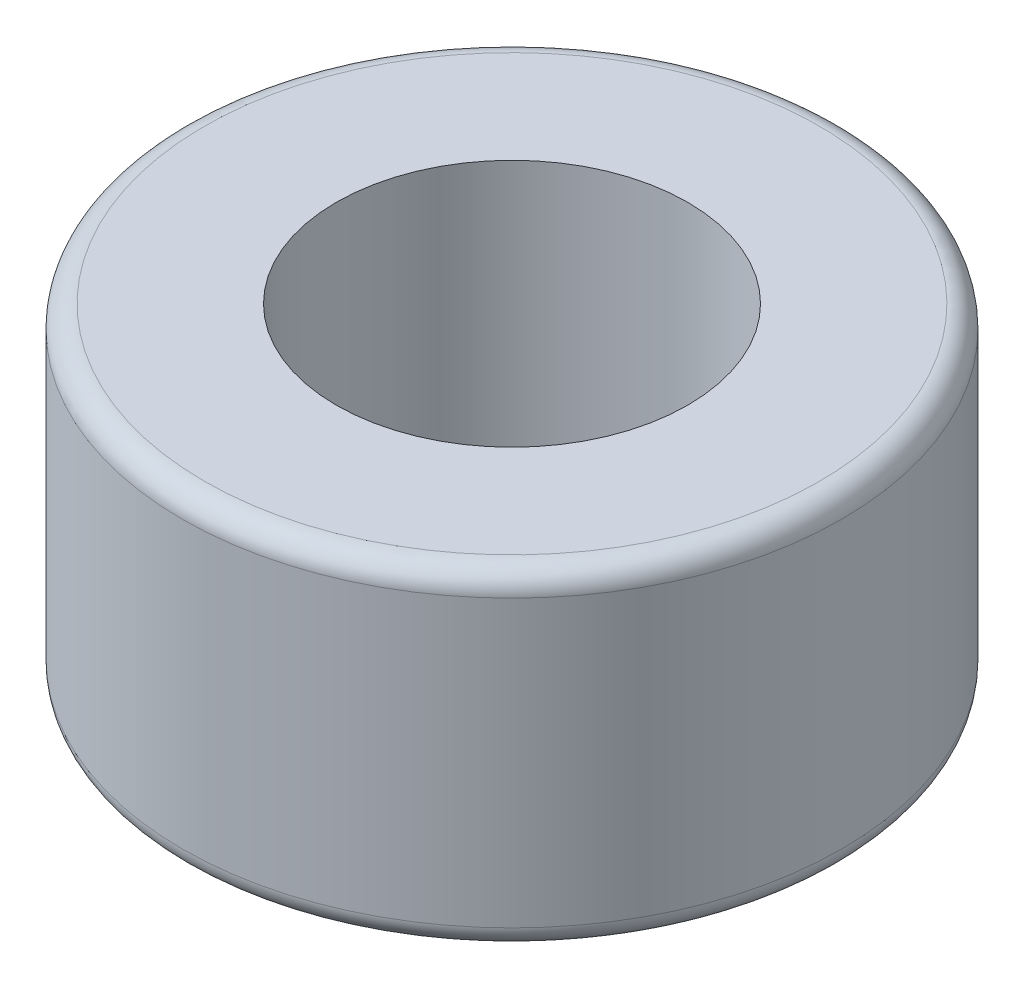
SolidWorks part; units mm, degrees
ref_plane "Front Plane" through (0, 0, 0) normal (0, 0, 1) x (1, 0, 0)
ref_plane "Top Plane" through (0, 0, 0) normal (0, 1, 0) x (1, 0, 0)
ref_plane "Right Plane" through (0, 0, 0) normal (1, 0, 0) x (0, 0, -1)
sketch "Sketch1" plane through (0, 0, 0) normal (0, 1, 0) x (1, 0, 0)
  circle A0 centre (0, 0) radius 3
  dimension "D1" = 6
extrude "Boss-Extrude1" add sketch "Sketch1" along normal blind 3
sketch "Sketch2" plane through (0, 3, 0) normal (0, 1, 0) x (1, 0, 0)
  circle A0 centre (0, 0) radius 1.6
  dimension "D1" = 3.2
extrude "Cut-Extrude1" cut sketch "Sketch2" against normal blind 3
fillet "Fillet1" radius 0.2 2 edges at (0, 0, 3) (0, 3, 3)
